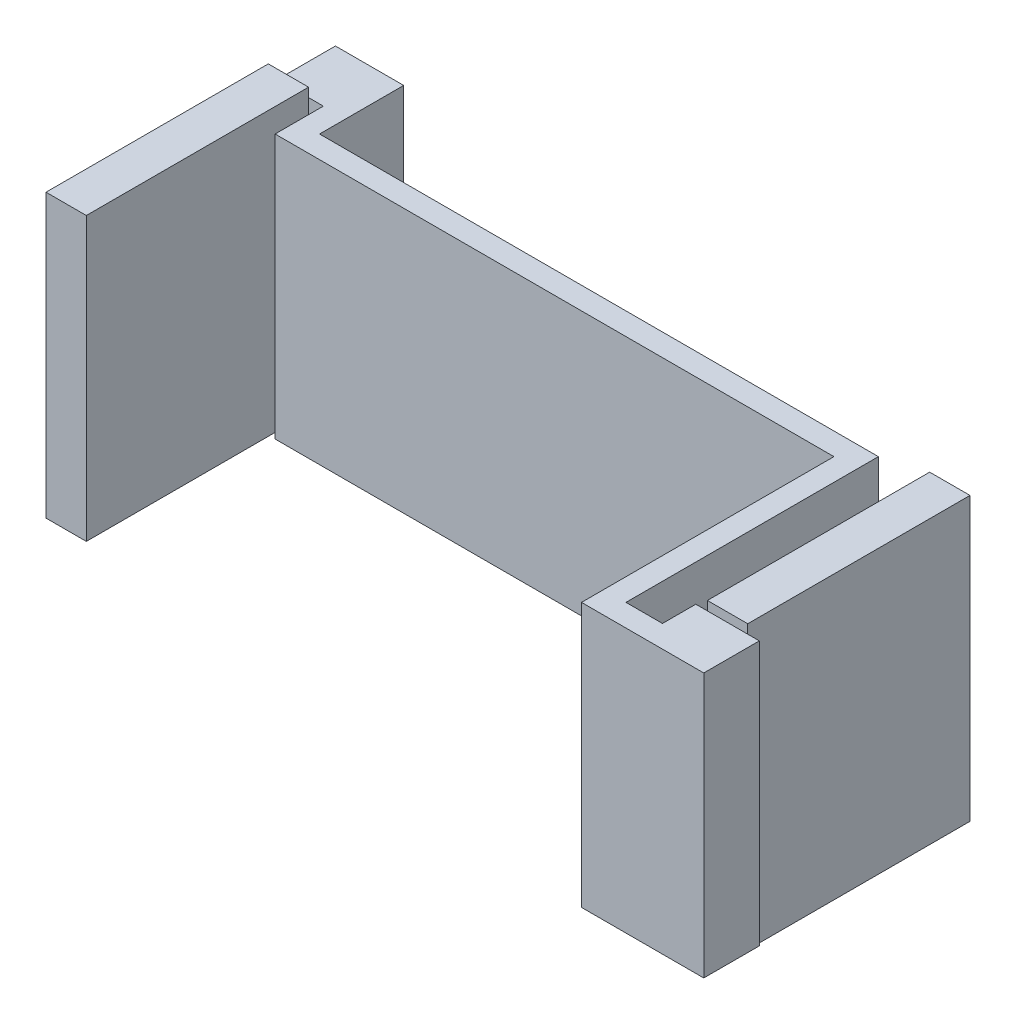
SolidWorks part; units mm, degrees
ref_plane "前基準面" through (0, 0, 0) normal (0, 0, 1) x (1, 0, 0)
ref_plane "上基準面" through (0, 0, 0) normal (0, 1, 0) x (1, 0, 0)
ref_plane "右基準面" through (0, 0, 0) normal (1, 0, 0) x (0, 0, -1)
sketch "草圖1" plane through (0, 0, 0) normal (0, 0, 1) x (1, 0, 0)
  line L0 (54.73, 36.11) -> (57.27, 36.11)
  line L1 (57.27, 36.11) -> (57.27, 53.89)
  line L2 (57.27, 53.89) -> (54.73, 53.89)
  line L3 (54.73, 53.89) -> (54.73, 36.11)
extrude "male housings in J5" add sketch "草圖1" along normal blind 14 from offset 10.1
sketch "草圖2" plane through (0, 0, 0) normal (0, 0, 1) x (1, 0, 0)
  line L0 (11.63, 36.11) -> (14.17, 36.11)
  line L1 (14.17, 36.11) -> (14.17, 53.89)
  line L2 (14.17, 53.89) -> (11.63, 53.89)
  line L3 (11.63, 53.89) -> (11.63, 36.11)
extrude "female housings on the module header" add sketch "草圖2" along normal blind 14 from offset 8.66
sketch "草圖3" plane through (0, 0, 0) normal (0, 0, 1) x (1, 0, 0)
  line L0 (12.2, 36.68) -> (16.5, 36.68)
  line L1 (16.5, 36.68) -> (16.5, 53.32)
  line L2 (16.5, 53.32) -> (12.2, 53.32)
  line L3 (12.2, 53.32) -> (12.2, 36.68)
extrude "S-bend above the female housings" add sketch "草圖3" along normal blind 3.66 from offset 5
sketch "草圖4" plane through (0, 0, 0) normal (0, 0, 1) x (1, 0, 0)
  line L0 (15.1, 36.68) -> (16.5, 36.68)
  line L1 (16.5, 36.68) -> (16.5, 53.32)
  line L2 (16.5, 53.32) -> (15.1, 53.32)
  line L3 (15.1, 53.32) -> (15.1, 36.68)
extrude "S-bend down leg" add sketch "草圖4" along normal blind 6.7 from offset 5
sketch "草圖5" plane through (0, 0, 0) normal (0, 0, 1) x (1, 0, 0)
  line L0 (15.1, 36.68) -> (51.7, 36.68)
  line L1 (51.7, 36.68) -> (51.7, 53.32)
  line L2 (51.7, 53.32) -> (15.1, 53.32)
  line L3 (15.1, 53.32) -> (15.1, 36.68)
extrude "run under the battery" add sketch "草圖5" along normal blind 1.4 from offset 10.3
sketch "草圖6" plane through (0, 0, 0) normal (0, 0, 1) x (1, 0, 0)
  line L0 (50.3, 36.68) -> (51.7, 36.68)
  line L1 (51.7, 36.68) -> (51.7, 53.32)
  line L2 (51.7, 53.32) -> (50.3, 53.32)
  line L3 (50.3, 53.32) -> (50.3, 36.68)
extrude "drop beside the module edge" add sketch "草圖6" along normal blind 17.3 from offset 10.3
sketch "草圖7" plane through (0, 0, 0) normal (0, 0, 1) x (1, 0, 0)
  line L0 (50.3, 36.68) -> (58, 36.68)
  line L1 (58, 36.68) -> (58, 53.32)
  line L2 (58, 53.32) -> (50.3, 53.32)
  line L3 (50.3, 53.32) -> (50.3, 36.68)
extrude "run under the male housings" add sketch "草圖7" along normal blind 1.4 from offset 26.2
sketch "草圖8" plane through (0, 0, 0) normal (0, 0, 1) x (1, 0, 0)
  line L0 (54, 36.68) -> (58, 36.68)
  line L1 (58, 36.68) -> (58, 53.32)
  line L2 (58, 53.32) -> (54, 53.32)
  line L3 (54, 53.32) -> (54, 36.68)
extrude "loop into the male housings" add sketch "草圖8" along normal blind 3.5 from offset 24.1
